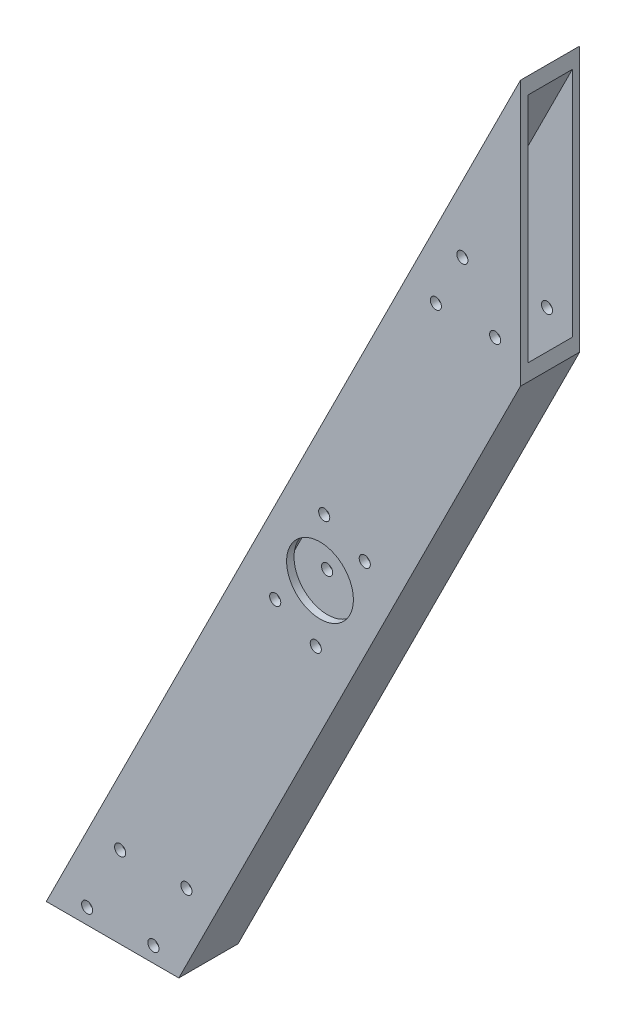
SolidWorks part; units mm, degrees
material "6063-T1"
ref_plane "Front Plane" through (0, 0, 0) normal (0, 0, 1) x (1, 0, 0)
ref_plane "Top Plane" through (0, 0, 0) normal (0, 1, 0) x (1, 0, 0)
ref_plane "Right Plane" through (0, 0, 0) normal (1, 0, 0) x (0, 0, -1)
sketch "Sketch1" plane through (0, 0, 0) normal (0, 0, 1) x (1, 0, 0)
  line L0 (0, 0) -> (203.2, 406.4)
  line L1 (203.2, 406.4) -> (203.2, 292.8077)
  line L2 (203.2, 292.8077) -> (56.7961, 0)
  line L3 (56.7961, 0) -> (0, 0)
  dimension "D1" = 203.2
  dimension "D2" = 406.4
  dimension "D3" = 50.8
extrude "Boss-Extrude1" add sketch "Sketch1" along normal blind 25.4
shell "Shell1" thickness 3.175
sketch "Sketch2" plane through (0, 0, 25.4) normal (0, 0, 1) x (1, 0, 0)
  line L0 (56.7961, 0) -> (203.2, 292.8077) construction
  line L1 (3.5498, 0) -> (53.2464, 0) construction
  circle A0 centre (117.2981, 177.8) radius 14.3129
  dimension "D2" = 28.6258
  dimension "D1" = 25.4
  dimension "D3" = 177.8
extrude "Cut-Extrude1" cut sketch "Sketch2" against normal through all
sketch "Sketch3" plane through (0, 0, 25.4) normal (0, 0, 1) x (1, 0, 0)
  line L0 (136.4866, 194.4421) -> (105.0742, 210.1483) construction
  line L1 (203.2, 406.4) -> (0, 0) construction
  circle A0 centre (117.2981, 177.8) radius 25.4 construction
  circle A1 centre (136.4866, 194.4421) radius 2.3813
  circle A2 centre (142.6342, 175.9994) radius 2.3812
  circle A3 centre (133.9402, 158.6115) radius 2.3813
  circle A4 centre (115.4975, 152.4639) radius 2.3813
  circle A5 centre (98.1095, 161.1579) radius 2.3813
  circle A6 centre (91.962, 179.6006) radius 2.3813
  circle A7 centre (100.6559, 196.9885) radius 2.3813
  circle A8 centre (119.0986, 203.1361) radius 2.3813
  point P22 (117.2981, 177.8)
  dimension "D1" = 50.8
  dimension "D2" = 4.7625
  dimension "D3" = 8
extrude "Cut-Extrude2" cut sketch "Sketch3" against normal through all contours A8 | A1 | A5 | A4
sketch "Sketch4" plane through (0, 0, 25.4) normal (0, 0, 1) x (1, 0, 0)
  line L0 (0, 0) -> (56.7961, 0) construction
  line L1 (203.2, 406.4) -> (0, 0) construction
  line L2 (56.7961, 0) -> (203.2, 292.8077) construction
  circle A0 centre (17.501, 6.604) radius 2.3813
  circle A1 centre (45.8991, 6.604) radius 2.3812
  circle A2 centre (31.6615, 34.925) radius 2.3812
  circle A3 centre (60.0596, 34.925) radius 2.3812
  circle A4 centre (166.9499, 305.5017) radius 2.3813
  circle A5 centre (178.3091, 328.2202) radius 2.3813
  circle A6 centre (192.3499, 305.5017) radius 2.3813
  point P22 (0, 0)
  point P23 (0, 0)
  dimension "D4" = 4.7625
  dimension "D5" = 4.7625
  dimension "D6" = 4.7625
  dimension "D7" = 4.7625
  dimension "D14" = 4.7625
  dimension "D17" = 4.7625
  dimension "D19" = 4.7625
  dimension "D1" = 6.604
  dimension "D2" = 34.925
  dimension "D3" = 6.604
  dimension "D8" = 12.7
  dimension "D9" = 12.7
  dimension "D10" = 12.7
  dimension "D11" = 12.7
  dimension "D12" = 302.514
  dimension "D13" = 12.7
  dimension "D15" = 25.4
  dimension "D16" = 12.7
  dimension "D21" = 25.4
extrude "Cut-Extrude3" cut sketch "Sketch4" against normal through all
